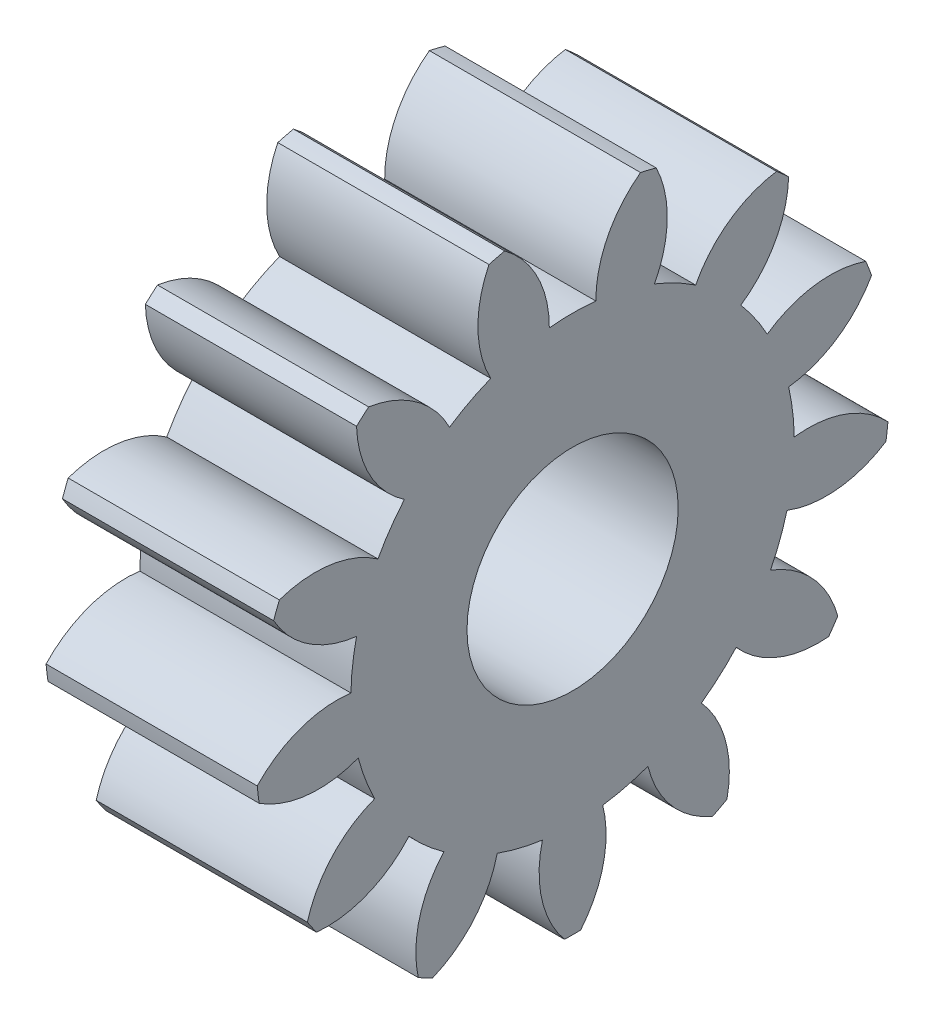
SolidWorks part; units mm, degrees
ref_plane "Plane1" through (0, 0, 0) normal (0, 0, 1) x (1, 0, 0)
ref_plane "Plane2" through (0, 0, 0) normal (0, 1, 0) x (1, 0, 0)
ref_plane "Plane3" through (0, 0, 0) normal (1, 0, 0) x (0, 0, -1)
sketch "HoldingSke" plane through (0, 0, 0) normal (0, 1, 0) x (1, 0, 0)
  line L0 (0, 0) -> (1.624, -0.3749)
  line L1 (-15, 0) -> (100, 0) construction
  line L2 (0, 0) -> (-2.1039, 2.3779)
  line L3 (0, 0) -> (-11.863, 4.5341)
  line L4 (0, 0) -> (8.4147, 1.9427)
  line L5 (0, 0) -> (-46.8476, -17.4728)
  line L6 (0, 0) -> (-2.4869, -1.6779)
  line L7 (-2.1039, 2.3779) -> (8.6586, 51.2059)
  line L8 (-76.2, 54.61) -> (-75.7, 54.61)
  line L9 (-71.009, 38.7566) -> (-53.1078, 45.2721)
  line L10 (-76.2, 71.12) -> (104.1128, 71.12)
  line L11 (0, 0) -> (-3, 0)
  line L12 (-76.2, 101.6) -> (-76.177, 101.6)
  line L13 (24.9733, 27.94) -> (52.9518, 28.4284)
  line L14 (24.9733, 27.94) -> (24.9743, 27.94)
  line L15 (24.9733, 27.94) -> (100.4006, 29.5858)
  line L16 (-63.627, -0.6) -> (-12.827, -0.6)
  circle A0 centre (0, 0) radius 1.5
  circle A1 centre (0, 0) radius 3.149
  circle A2 centre (0, 0) radius 37.5
  circle A3 centre (0, 0) radius 1.5
  dimension "MHD" = 6.298
  dimension "Hub_dia" = 75
  dimension "Bore" = 3
  dimension "MBD" = 3
  dimension "Num_teeth" = 13
  dimension "Pitch" = 1.6667
  dimension "Overall_len" = 50
  dimension "Show_teeth" = 13
  dimension "Thickness" = 3
  dimension "OAL" = 50.0001
  dimension "T_dim" = 0.5
  dimension "Ap" = 20
  dimension "H" = 19.05
  dimension "Pitch_radius" = 180.3128
  dimension "Width" = 3
  dimension "Backlash" = 0.023
  dimension "Addendum_fac" = 1
  dimension "Dedendum_fac" = 1.25
  dimension "Clearance_fac" = 0.25
  dimension "Dedendum_add" = 0.001
  dimension "Module" = 0.6
sketch "BasProSke" plane through (0, 0, 0) normal (0, 1, 0) x (1, 0, 0)
  line L0 (-10, 0) -> (60, 0) construction
  line L1 (0, 0) -> (0, 4.5)
  line L2 (0, 0) -> (3, 0)
  line L3 (3, 0) -> (3, 4.5)
  line L4 (3, 4.5) -> (0, 4.5)
  dimension "Thickness" = 3
  dimension "Diameter" = 9
revolve "Base-Revolve" add sketch "BasProSke" angle 360 about L0
sketch "TooCutSke" plane through (0, 0, 0) normal (1, 0, 0) x (0, 0, -1)
  line L1 (0, 0) -> (0, 107) construction
  line L2 (0, 0) -> (-0.5103, 3.8665) construction
  line L3 (0, 0) -> (-1.8553, 7.5272) construction
  line L4 (-0.5103, 3.8665) -> (-0.9276, 3.7636) construction
  arc A0 (0.3306, 3.1316) -> (-0.3306, 3.1316) centre (0, 0) ccw
  arc A1 (0.9926, 4.4152) -> (-0.9926, 4.4152) centre (0, 0) ccw
  circle A2 centre (0, 0) radius 3.9 construction
  circle A3 centre (0, 0) radius 3.6648 construction
  arc A4 (-0.3306, 3.1316) -> (-0.9926, 4.4152) centre (-1.8906, 3.1395) ccw
  arc A5 (0.9926, 4.4152) -> (0.3306, 3.1316) centre (1.8906, 3.1395) ccw
  dimension "Root_dia" = 6.298
  dimension "Overcut_dia" = 9.0508
  dimension "Pitch_dia" = 7.8
  dimension "Base_dia" = 7.3296
  dimension "Flank_rad" = 1.56
  dimension "Half_ang" = 13.846
  dimension "Half_CT" = 0.4298
extrude "ToothCut" cut sketch "TooCutSke" along normal through all
fillet "Breaks" [suppressed] radius 0.012
fillet "RootFillets" [suppressed] radius 0.151
pattern_circular "TeethCuts" count 13 every 27.692 about axis through (-10, 0, 0) along (1, 0, 0) of "ToothCut", "RootFillets", "Breaks"
sketch "HubNeaOneSke" plane through (0, 0, 0) normal (-1, 0, 0) x (0, 0, 1)
  circle A0 centre (0, 0) radius 3.149
  dimension "Diameter" = 6.298
extrude "HubNearOne" [suppressed] add sketch "HubNeaOneSke" along normal blind 47.0001
sketch "HubNeaBotSke" plane through (0, 0, 0) normal (-1, 0, 0) x (0, 0, 1)
  circle A0 centre (0, 0) radius 3.149
  dimension "Diameter" = 6.298
extrude "HubNearBoth" [suppressed] add sketch "HubNeaBotSke" along normal blind 23.5
ref_plane "FarPln" through (3, 0, 0) normal (1, 0, 0) x (0, 0, -1)
sketch "HubFarSke" plane through (3, 0, 0) normal (1, 0, 0) x (0, 0, -1)
  circle A0 centre (0, 0) radius 3.149
  dimension "Diameter" = 6.298
extrude "HubFar" [suppressed] add sketch "HubFarSke" along normal blind 23.5
sketch "BorSke" plane through (0, 0, 0) normal (1, 0, 0) x (0, 0, -1)
  circle A0 centre (0, 0) radius 1.5
  dimension "Diameter" = 3
extrude "Bore" cut sketch "BorSke" along normal mid plane 100.0001
sketch "KeySke" plane through (0, 0, 0) normal (1, 0, 0) x (0, 0, -1)
  line L0 (-0.6, 0) -> (-0.6, 2)
  line L1 (-0.6, 2) -> (0.6, 2)
  line L2 (0.6, 2) -> (0.6, 0)
  line L3 (0, 0) -> (0, 34) construction
  line L4 (-0.6, 0) -> (0.6, 0)
  dimension "Offset" = 2
  dimension "Width" = 1.2
extrude "Keyway" [suppressed] cut sketch "KeySke" along normal mid plane 100.0001
pattern_circular "Keyway2" [suppressed] count 2 every 90 about axis through (-10, 0, 0) along (1, 0, 0)
equation "' \"Module@HoldingSke\" = 6.35"
equation "' \"Num_teeth@HoldingSke\" = 12"
equation "' \"Ap@HoldingSke\" =  20"
equation "' \"Ap@HoldingSke\" = 20"
equation "' \"Width@HoldingSke\" = 0.5 * 25.4"
equation "' \"Hub_dia@HoldingSke\"= 1 * 25.4"
equation "' \"Hub_dia@HoldingSke\" = 1 * 25.4"
equation "' \"Overall_len@HoldingSke\" = 1.0 * 25.4"
equation "' \"Bore@HoldingSke\" = 0.75 * 25.4"
equation "' \"T_dim@HoldingSke\" = 0.1 * 25.4"
equation "' \"Width@KeySke\" = 0.25 * 25.4"
equation "' \"Show_teeth@HoldingSke\" = 13"
equation "' \"Backlash@HoldingSke\" = 0.009 * 25.4"
equation "' \"Addendum_fac@HoldingSke\" = 1.0"
equation "' \"Dedendum_fac@HoldingSke\" = 1.25"
equation "' \"Dedendum_add@HoldingSke\" = 0.00005 * 25.4"
equation "' \"Clearance_fac@HoldingSke\" = 0.25"
equation "\"Pitch@HoldingSke\" = 1 / \"Module@HoldingSke\""
equation "\"Overcut_dia@TooCutSke\" = (\"Num_teeth@HoldingSke\" + 2 * \"Addendum_fac@HoldingSke\") / \"Pitch@HoldingSke\" + 0.002 * 25.4"
equation "\"Pitch_dia@TooCutSke\" = \"Num_teeth@HoldingSke\" / \"Pitch@HoldingSke\""
equation "\"Base_dia@TooCutSke\" = \"Num_teeth@HoldingSke\" / \"Pitch@HoldingSke\" * cos((\"Ap@HoldingSke\"  * 3.14159265 / 180))"
equation "\"Root_dia@TooCutSke\" = (\"Num_teeth@HoldingSke\" + 2) / \"Pitch@HoldingSke\" - 2 * (\"Addendum_fac@HoldingSke\" + \"Dedendum_fac@HoldingSke\") / \"Pitch@HoldingSke\" - \"Dedendum_add@HoldingSke\" * 2"
equation "\"Half_ang@TooCutSke\" = 180 / \"Num_teeth@HoldingSke\""
equation "\"Half_CT@TooCutSke\" = \"Num_teeth@HoldingSke\" / \"Pitch@HoldingSke\" * sin((3.14159265 / 2 / \"Num_teeth@HoldingSke\")) / 2 - 7 * \"Backlash@HoldingSke\" / 4"
equation "\"Flank_rad@TooCutSke\" = \"Num_teeth@HoldingSke\" / \"Pitch@HoldingSke\" / 5"
equation "\"Radius@RootFillets\" = \"Clearance_fac@HoldingSke\" / \"Pitch@HoldingSke\" + \"Dedendum_add@HoldingSke\""
equation "\"Break_rad@Breaks\" = 0.02 / \"Pitch@HoldingSke\""
equation "\"Thickness@HoldingSke\" = \"Width@HoldingSke\""
equation "\"OAL@HoldingSke\" = \"Thickness@HoldingSke\""
equation "\"MHD@HoldingSke\" = (\"Num_teeth@HoldingSke\" + 2) / \"Pitch@HoldingSke\" - 2 * (\"Addendum_fac@HoldingSke\" + \"Dedendum_fac@HoldingSke\")  / \"Pitch@HoldingSke\" - \"Dedendum_add@HoldingSke\" * 2"
equation "\"MBD@HoldingSke\" = (\"Num_teeth@HoldingSke\" + 2) / \"Pitch@HoldingSke\" - 2 * (\"Addendum_fac@HoldingSke\" + \"Dedendum_fac@HoldingSke\")  / \"Pitch@HoldingSke\" - \"Dedendum_add@HoldingSke\" * 2 - 0.002 * 25.4"
equation "\"MHD@HoldingSke\" = ((sgn( \"MHD@HoldingSke\" - \"Hub_dia@HoldingSke\" )-1)*( \"MHD@HoldingSke\" - \"Hub_dia@HoldingSke\" ))/-2+ \"Hub_dia@HoldingSke\""
equation "\"MBD@HoldingSke\" = ((sgn( \"MBD@HoldingSke\" - \"Bore@HoldingSke\" )-1)*( \"MBD@HoldingSke\" - \"Bore@HoldingSke\" ))/-2+ \"Bore@HoldingSke\""
equation "\"OAL@HoldingSke\" = ((sgn( \"OAL@HoldingSke\" - \"Overall_len@HoldingSke\" )+1)*( \"OAL@HoldingSke\" - \"Overall_len@HoldingSke\" ))/2 + \"Overall_len@HoldingSke\" + 0.000002 * 25.4"
equation "\"Num_teeth@TeethCuts\" = int( \"Show_teeth@HoldingSke\" ) + 1"
equation "\"Num_teeth@TeethCuts\" = ((sgn( \"Num_teeth@TeethCuts\" - \"Num_teeth@HoldingSke\" )-1)*( \"Num_teeth@TeethCuts\" - \"Num_teeth@HoldingSke\" ))/-2+ \"Num_teeth@HoldingSke\""
equation "\"Num_teeth@TeethCuts\" = ((sgn( \"Num_teeth@TeethCuts\" - 2.0)+1)*( \"Num_teeth@TeethCuts\" - 2.0))/2 +2.0"
equation "\"Angle@TeethCuts\" = 360.0 / \"Num_teeth@HoldingSke\""
equation "\"Diameter@BasProSke\" = (\"Num_teeth@HoldingSke\" + 2 * \"Addendum_fac@HoldingSke\") / \"Pitch@HoldingSke\""
equation "\"Thickness@BasProSke\"  = \"Thickness@HoldingSke\""
equation "' \"Fillet_rad@BasProSke\" =  \"Thickness@HoldingSke\" * 0.05"
equation "' \"Fillet_rad@BasProSke\" = \"Thickness@HoldingSke\" * 0.05"
equation "\"MHD@HoldingSke\" = ((sgn( \"MHD@HoldingSke\" - \"Root_dia@TooCutSke\" )-1)*( \"MHD@HoldingSke\" - \"Root_dia@TooCutSke\" ))/-2+ \"Root_dia@TooCutSke\""
equation "\"Diameter@HubNeaOneSke\" = \"MHD@HoldingSke\""
equation "\"Length@HubNearOne\" = \"OAL@HoldingSke\" - \"Thickness@BasProSke\""
equation "\"Diameter@HubNeaBotSke\" = \"MHD@HoldingSke\""
equation "\"Length@HubNearBoth\" = ( \"OAL@HoldingSke\" - \"Thickness@BasProSke\" ) / 2.0"
equation "\"Thickness@FarPln\" = \"Thickness@BasProSke\""
equation "\"Diameter@HubFarSke\" = \"MHD@HoldingSke\""
equation "\"Length@HubFar\" = ( \"OAL@HoldingSke\" - \"Thickness@BasProSke\" ) / 2.0"
equation "\"Diameter@BorSke\" = \"MBD@HoldingSke\""
equation "\"D1@Bore\" = \"OAL@HoldingSke\" * 2.0"
equation "\"D1@Keyway\" = \"OAL@HoldingSke\" * 2.0"
equation "\"Offset@KeySke\" = \"T_dim@HoldingSke\" + \"MBD@HoldingSke\" / 2.0"
